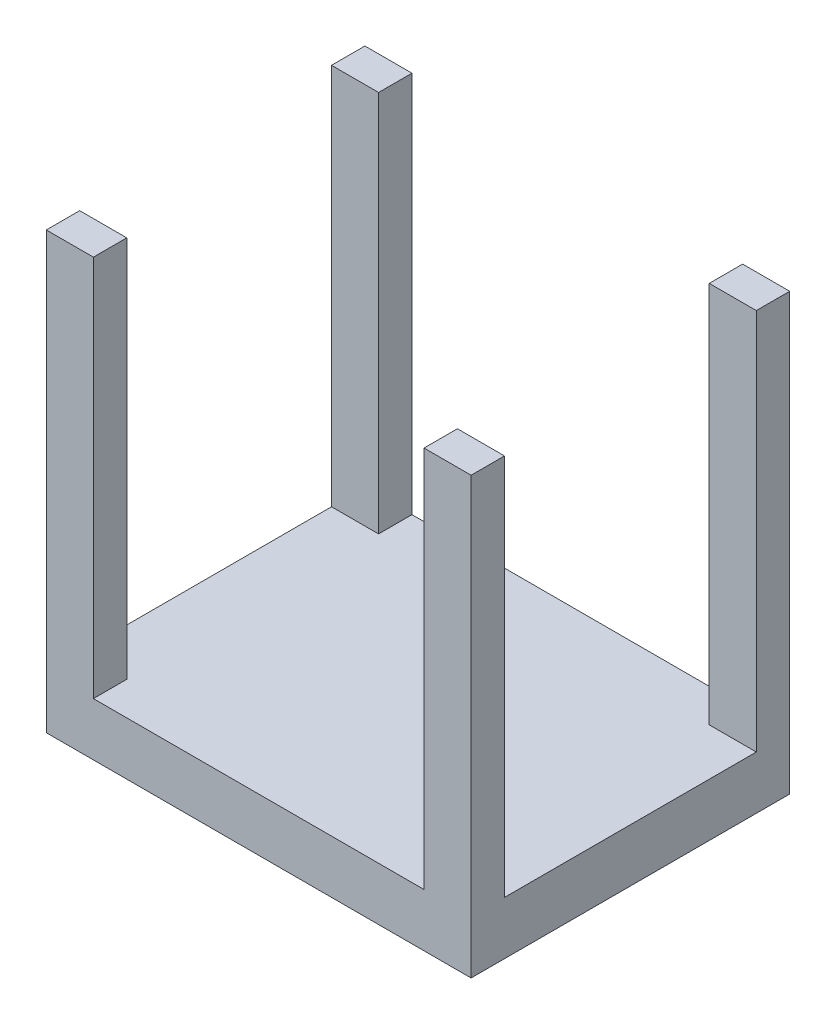
SolidWorks part; units mm, degrees
ref_plane "Front Plane" through (0, 0, 0) normal (0, 0, 1) x (1, 0, 0)
ref_plane "Top Plane" through (0, 0, 0) normal (0, 1, 0) x (1, 0, 0)
ref_plane "Right Plane" through (0, 0, 0) normal (1, 0, 0) x (0, 0, -1)
sketch "Sketch1" plane through (0, 0, 0) normal (0, 1, 0) x (1, 0, 0)
  line L1 (-1000, 750) -> (1000, 750)
  line L2 (-1000, 750) -> (-1000, -750)
  line L3 (-1000, -750) -> (1000, -750)
  line L4 (1000, 750) -> (1000, -750)
  line L5 (-1000, 750) -> (1000, -750) construction
  line L6 (-1000, -750) -> (1000, 750) construction
  point P0 (0, 0)
  dimension "D1" = 2000
  dimension "D2" = 1500
extrude "Boss-Extrude1" add sketch "Sketch1" along normal blind 250
sketch "Sketch2" plane through (0, 250, 0) normal (0, 1, 0) x (1, 0, 0)
  line L0 (0, 750) -> (0, -750) construction
  line L1 (-1000, 750) -> (-778.3637, 750)
  line L2 (-1000, 750) -> (-1000, 592.7712)
  line L3 (-1000, 592.7712) -> (-778.3637, 592.7712)
  line L4 (-778.3637, 750) -> (-778.3637, 592.7712)
  line L5 (1000, 750) -> (-1000, 750) construction
  line L6 (-1000, -750) -> (1000, -750) construction
  line L7 (-1000, 0) -> (1000, 0) construction
  line L8 (-1000, 750) -> (-1000, -750) construction
  line L9 (1000, -750) -> (1000, 750) construction
  line L10 (1000, 750) -> (778.3637, 750)
  line L11 (1000, 750) -> (1000, 592.7712)
  line L12 (1000, 592.7712) -> (778.3637, 592.7712)
  line L13 (778.3637, 750) -> (778.3637, 592.7712)
  line L14 (1000, -592.7712) -> (778.3637, -592.7712)
  line L15 (1000, -750) -> (1000, -592.7712)
  line L16 (1000, -750) -> (778.3637, -750)
  line L17 (778.3637, -750) -> (778.3637, -592.7712)
  line L18 (-778.3637, -750) -> (-778.3637, -592.7712)
  line L19 (-1000, -750) -> (-1000, -592.7712)
  line L20 (-1000, -750) -> (-778.3637, -750)
  line L21 (-1000, -592.7712) -> (-778.3637, -592.7712)
extrude "Boss-Extrude3" add sketch "Sketch2" along normal blind 1800
sketch "Sketch3" plane through (0, 0, 0) normal (0, -1, 0) x (1, 0, 0)
  text T0 "AJAY 464" font "Consolas" height 75
extrude "Boss-Extrude4" add sketch "Sketch3" along normal blind 40
